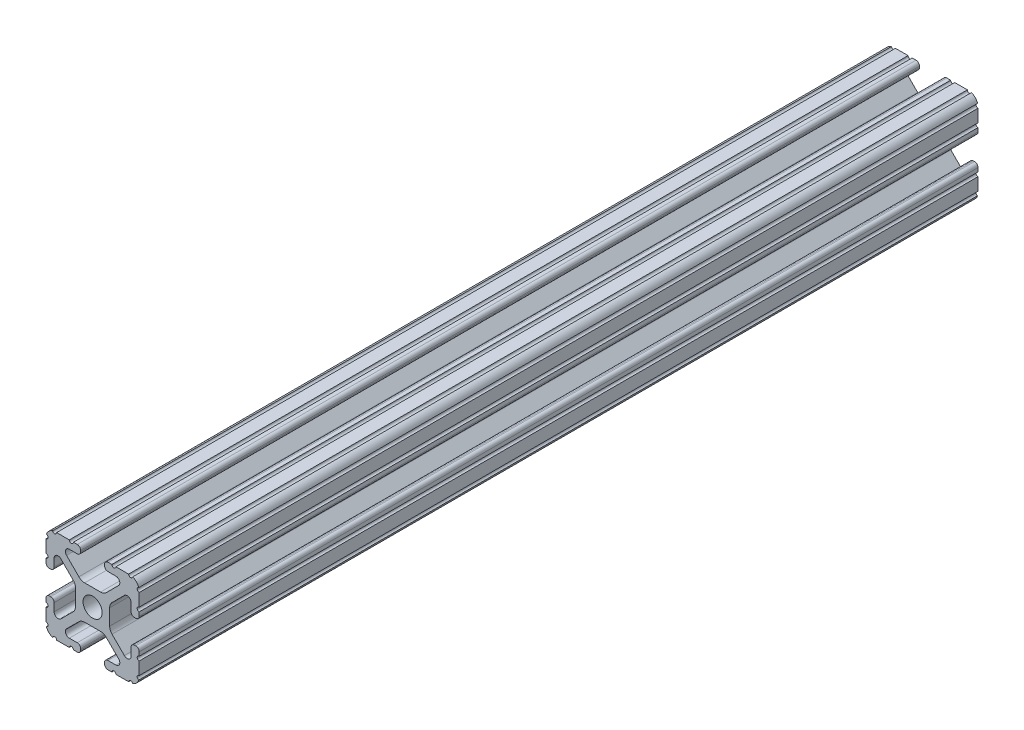
SolidWorks part; units mm, degrees
ref_plane "Front Plane" through (0, 0, 0) normal (0, 0, 1) x (1, 0, 0)
ref_plane "Top Plane" through (0, 0, 0) normal (0, 1, 0) x (1, 0, 0)
ref_plane "Right Plane" through (0, 0, 0) normal (1, 0, 0) x (0, 0, -1)
sketch "Sketch2" plane through (0, 0, 0) normal (0, 0, 1) x (1, 0, 0)
  line L0 (0, 12.7) -> (0, -12.7) construction
  line L1 (-12.7, 0) -> (12.7, 0) construction
  line L2 (3.2512, -12.7) -> (12.7, -12.7)
  line L3 (12.7, -12.7) -> (12.7, -3.2512)
  line L4 (3.2512, -12.7) -> (3.2512, -10.4902)
  line L5 (3.2512, -10.4902) -> (8.9276, -10.4902)
  line L6 (8.9276, -10.4902) -> (3.0856, -4.6482)
  line L7 (0, 0) -> (12.7, -12.7) construction
  line L8 (12.7, -3.2512) -> (10.4902, -3.2512)
  line L9 (10.4902, -3.2512) -> (10.4902, -8.9276)
  line L10 (10.4902, -8.9276) -> (4.6482, -3.0856)
  circle A0 centre (0, 0) radius 2.6035
  arc A1 (6.3485, -10.4902) -> (7.1039, -8.6665) centre (6.3485, -9.4219) ccw construction
  point P8 (0, -4.6482)
  dimension "Center Hole Diameter" = 5.207
  dimension "Rail Height" = 25.4
  dimension "Rail Width" = 25.4
  dimension "T-Slot Width" = 6.5024
  dimension "Slot Inner Width" = 14.8336
  dimension "Thickness" = 2.2098
  dimension "Slot Depth" = 5.842
  dimension "D1" = 2.2098
sketch "Sketch3" plane through (0, 0, 0) normal (1, 0, 0) x (0, 0, -1)
  line L0 (-114.3, -12.7) -> (114.3, -12.7) construction
  line L1 (-102.87, 0) -> (102.87, 0) construction
  dimension "Length" = 228.6
  dimension "D1" = 205.74
sketch "Sketch4" plane through (0, 0, 0) normal (0, 0, 1) x (1, 0, 0)
  line L0 (4.1904, -12.7) -> (10.1173, -12.7)
  line L1 (3.2512, -12.7) -> (12.7, -12.7) construction
  line L2 (3.2512, -12.7) -> (3.2512, -10.4902) construction
  line L3 (3.2512, -10.4902) -> (8.9276, -10.4902) construction
  line L4 (3.2512, -11.4294) -> (3.2512, -11.7608)
  line L5 (4.1904, -10.4902) -> (6.3485, -10.4902)
  line L6 (0, -4.6482) -> (2.164, -4.6482)
  line L7 (8.9276, -10.4902) -> (3.0856, -4.6482) construction
  line L8 (3.7373, -5.2999) -> (7.1039, -8.6665)
  line L9 (12.7, -12.7) -> (12.7, -3.2512) construction
  line L10 (10.4902, -8.9276) -> (4.6482, -3.0856) construction
  line L11 (10.4902, -3.2512) -> (10.4902, -8.9276) construction
  line L12 (10.4902, -6.3485) -> (10.4902, -4.1904)
  line L13 (12.7, -3.2512) -> (10.4902, -3.2512) construction
  line L14 (11.4294, -3.2512) -> (11.7608, -3.2512)
  line L15 (12.7, -4.1904) -> (12.7, -10.1173)
  line L16 (8.6665, -7.1039) -> (5.2999, -3.7373)
  line L17 (4.6482, 0) -> (4.6482, -2.164)
  line L18 (-12.7, 0) -> (12.7, 0) construction
  line L19 (0, -4.6482) -> (0, -2.6035)
  line L20 (0, 12.7) -> (0, -12.7) construction
  line L21 (4.6482, 0) -> (2.6035, 0)
  arc A0 (3.2512, -11.7608) -> (4.1904, -12.7) centre (4.1904, -11.7608) ccw
  arc A2 (3.2512, -11.4294) -> (4.1904, -10.4902) centre (4.1904, -11.4294) cw
  arc A3 (6.3485, -10.4902) -> (7.1039, -8.6665) centre (6.3485, -9.4219) ccw
  arc A4 (2.164, -4.6482) -> (3.7373, -5.2999) centre (2.164, -6.8732) cw
  arc A5 (10.1173, -12.7) -> (12.7, -10.1173) centre (10.1173, -10.1173) ccw
  arc A6 (8.6665, -7.1039) -> (10.4902, -6.3485) centre (9.4219, -6.3485) ccw
  arc A7 (10.4902, -4.1904) -> (11.4294, -3.2512) centre (11.4294, -4.1904) cw
  arc A8 (11.7608, -3.2512) -> (12.7, -4.1904) centre (11.7608, -4.1904) cw
  arc A9 (5.2999, -3.7373) -> (4.6482, -2.164) centre (6.8732, -2.164) cw
  circle A10 centre (0, 0) radius 2.6035 construction
  arc A11 (0, -2.6035) -> (2.6035, 0) centre (0, 0) ccw
  dimension "D1" = 2.5827
  dimension "D2" = 2.225
  dimension "D3" = 0.9392
extrude "Boss-Extrude1" add sketch "Sketch4" along normal mid plane 228.6
sketch "Sketch5" plane through (0, 0, 0) normal (0, 0, 1) x (1, 0, 0)
  line L0 (3.2512, -12.7) -> (12.7, -12.7) construction
  line L1 (4.1904, -10.4902) -> (6.3485, -10.4902) construction
  line L3 (0, 0) -> (12.7, -12.7) construction
  line L4 (6.3485, -10.4902) -> (6.3485, -12.7) construction
  line L5 (8.9276, -10.4902) -> (3.0856, -4.6482) construction
  circle A0 centre (10.3562, -12.7) radius 0.5524
  circle A1 centre (5.796, -12.7) radius 0.5524
  circle A2 centre (12.7, -10.3562) radius 0.5524
  circle A3 centre (12.7, -5.796) radius 0.5524
  point P10 (5.2694, -10.4902)
  point P12 (9.4219, -6.3485)
  dimension "D1" = 1.1049
extrude "Cut-Extrude1" cut sketch "Sketch5" against normal through all both and the other way through all
mirror "Mirror1" about plane through (0, 0, 0) normal (1, 0, 0) of bodies 137 134
mirror "Mirror2" about plane through (0, 0, 0) normal (0, 1, 0) of bodies 135
equation "\"D1@Boss-Extrude1\"=\"Length@Sketch3\""
equation "\"D1@Sketch2\"=\"Thickness@Sketch2\""
equation "\"D2@Sketch4\"=\"Slot Inner Width@Sketch2\"*0.15"
equation "\"D1@Sketch4\"=\"D3@Sketch4\"*2.75"
equation "\"D3@Sketch4\"=\"Thickness@Sketch2\"*0.425"
equation "\"D1@Sketch5\"=\"Thickness@Sketch2\"*0.5"
equation "\"D1@Sketch3\"=\"Length@Sketch3\"*0.9"
